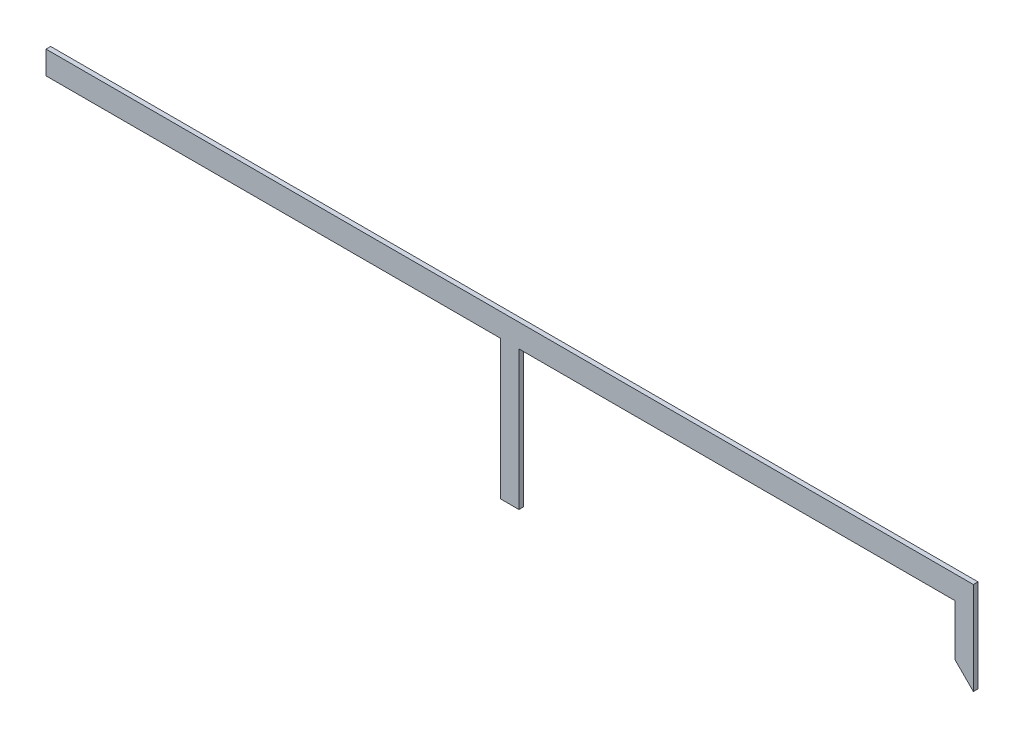
SolidWorks part; units mm, degrees
material "1.0558 (G300)"
ref_plane "前视基准面" through (0, 0, 0) normal (0, 0, 1) x (1, 0, 0)
ref_plane "上视基准面" through (0, 0, 0) normal (0, 1, 0) x (1, 0, 0)
ref_plane "右视基准面" through (0, 0, 0) normal (1, 0, 0) x (0, 0, -1)
sketch "草图1" plane through (0, 0, 0) normal (0, 0, 1) x (1, 0, 0)
  line L0 (-500, 0) -> (500, 0)
  line L1 (500, 0) -> (500, -100)
  line L2 (500, -100) -> (480, -80)
  line L3 (480, -80) -> (480, -25)
  line L4 (480, -25) -> (10, -25)
  line L5 (10, -25) -> (10, -175)
  line L6 (10, -175) -> (-10, -175)
  line L7 (0, 0) -> (0, -143.8119) construction
  line L8 (-10, -25) -> (-10, -175)
  line L9 (-500, -25) -> (-10, -25)
  line L13 (-500, 0) -> (-500, -25)
  point P11 (0, -175)
  dimension "D1" = 500
  dimension "D2" = 100
  dimension "D3" = 20
  dimension "D4" = 45
  dimension "D5" = 25
  dimension "D6" = 20
  dimension "D7" = 150
extrude "凸台-拉伸1" add sketch "草图1" along normal blind 5
